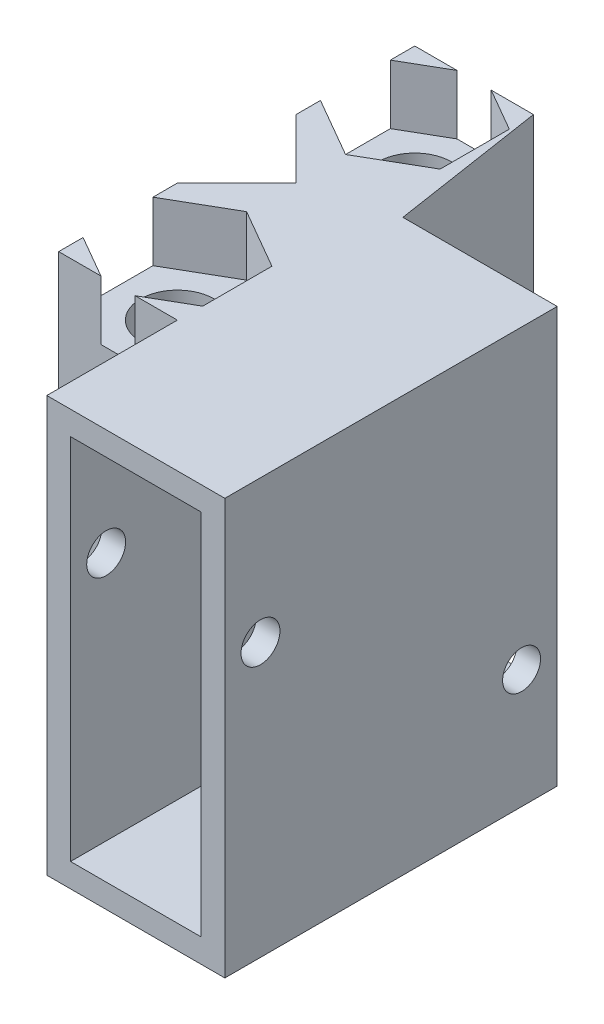
SolidWorks part; units mm, degrees
ref_plane "Plan de face" through (0, 0, 0) normal (0, 0, 1) x (1, 0, 0)
ref_plane "Plan de dessus" through (0, 0, 0) normal (0, 1, 0) x (1, 0, 0)
ref_plane "Plan de droite" through (0, 0, 0) normal (1, 0, 0) x (0, 0, -1)
sketch "Esquisse1" plane through (0, 0, 0) normal (0, 0, 1) x (1, 0, 0)
  line L0 (0, 0) -> (11, 0)
  line L1 (11, 0) -> (11, 31)
  line L2 (11, 31) -> (0, 31)
  line L3 (0, 31) -> (0, 0)
  dimension "D1" = 31
  dimension "D2" = 11
extrude "Extru.-Mince1" add sketch "Esquisse1" along normal blind 28 thin
sketch "Esquisse2" plane through (0, 0, 0) normal (0, 0, -1) x (-1, 0, 0)
  line L0 (0, 31) -> (0, 0) construction
  line L1 (-11, 0) -> (0, 0)
  line L2 (-11, 0) -> (-11, 5)
  line L3 (-11, 5) -> (0, 5)
  line L4 (0, 0) -> (0, 5)
  dimension "D1" = 5
extrude "Boss.-Extru.1" add sketch "Esquisse2" against normal blind 14
sketch "Esquisse8" plane through (0, -2, 0) normal (0, -1, 0) x (1, 0, 0)
  line L0 (-2, 28) -> (-2, 0) construction
  line L1 (-2, 12) -> (-22.0736, 12) construction
  line L2 (-2, 17) -> (-12, 17)
  line L3 (-12, 17) -> (-12, 7)
  line L4 (-12, -13) -> (-2, -13)
  line L5 (-2, -13) -> (0, 0)
  line L6 (-2, 0) -> (13, 0) construction
  line L7 (0, 0) -> (-2, 0)
  line L8 (-2, 0) -> (-2, 17)
  line L9 (-12, 7) -> (-7, 2)
  line L10 (-7, 2) -> (-12, -3)
  line L11 (-12, -3) -> (-12, -13)
  circle A0 centre (-7, 12) radius 3.1
  circle A1 centre (-7, -8) radius 3.1
  dimension "D1" = 6.2
  dimension "D2" = 6.2
  dimension "D3" = 5
  dimension "D4" = 20
  dimension "D5" = 12
  dimension "D6" = 10
  dimension "D7" = 5
  dimension "D8" = 5
  dimension "D9" = 2
  dimension "D10" = 10
  dimension "D11" = 5
  dimension "D12" = 15
  dimension "D13" = 10
extrude "Boss.-Extru.2" add sketch "Esquisse8" against normal up to surface (35 mm away) up to face at (5.5, 33, 14)
sketch "Esquisse3" plane through (13, 0, 0) normal (1, 0, 0) x (0, 0, -1)
  line L0 (-28, -2) -> (-28, 33) construction
  line L1 (0, -2) -> (0, 33) construction
  line L3 (0, 8) -> (-3, 8) construction
  line L4 (-28, -2) -> (0, -2) construction
  circle A0 centre (-3, 8) radius 1.6
  circle A1 centre (-25, 21) radius 1.6392
  dimension "D1" = 3.2
  dimension "D2" = 3
  dimension "D3" = 3
  dimension "D4" = 10
  dimension "D5" = 23
extrude "Enlèv. mat.-Extru.1" cut sketch "Esquisse3" against normal through all
sketch "Esquisse9" plane through (0, -2, 0) normal (0, -1, 0) x (1, 0, 0)
  line L0 (-12, 17) -> (-12, 7) construction
  line L1 (-7, -2.1688) -> (-12.05, -5.0844)
  line L2 (-12.05, -5.0844) -> (-12.05, -10.9156)
  line L3 (-12.05, -10.9156) -> (-7, -13.8312)
  line L4 (-7, -13.8312) -> (-1.95, -10.9156)
  line L5 (-1.95, -10.9156) -> (-1.95, -5.0844)
  line L6 (-1.95, -5.0844) -> (-7, -2.1688)
  line L7 (-1.95, 14.9156) -> (-7, 17.8312)
  line L8 (-7, 17.8312) -> (-12.05, 14.9156)
  line L9 (-12.05, 14.9156) -> (-12.05, 9.0844)
  line L10 (-12.05, 9.0844) -> (-7, 6.1688)
  line L11 (-7, 6.1688) -> (-1.95, 9.0844)
  line L12 (-1.95, 9.0844) -> (-1.95, 14.9156)
  circle A0 centre (-7, -8) radius 5.05 construction
  circle A1 centre (-7, 12) radius 5.05 construction
  dimension "D1" = 10.1
  dimension "D2" = 10.1
extrude "Enlèv. mat.-Extru.2" cut sketch "Esquisse9" against normal blind 5
ref_plane "Plan1" through (0, 15.5, 0) normal (0, -1, 0) x (-1, 0, 0)
mirror "Symétrie1" about plane through (0, 15.5, 0) normal (0, -1, 0) of "Enlèv. mat.-Extru.2"
